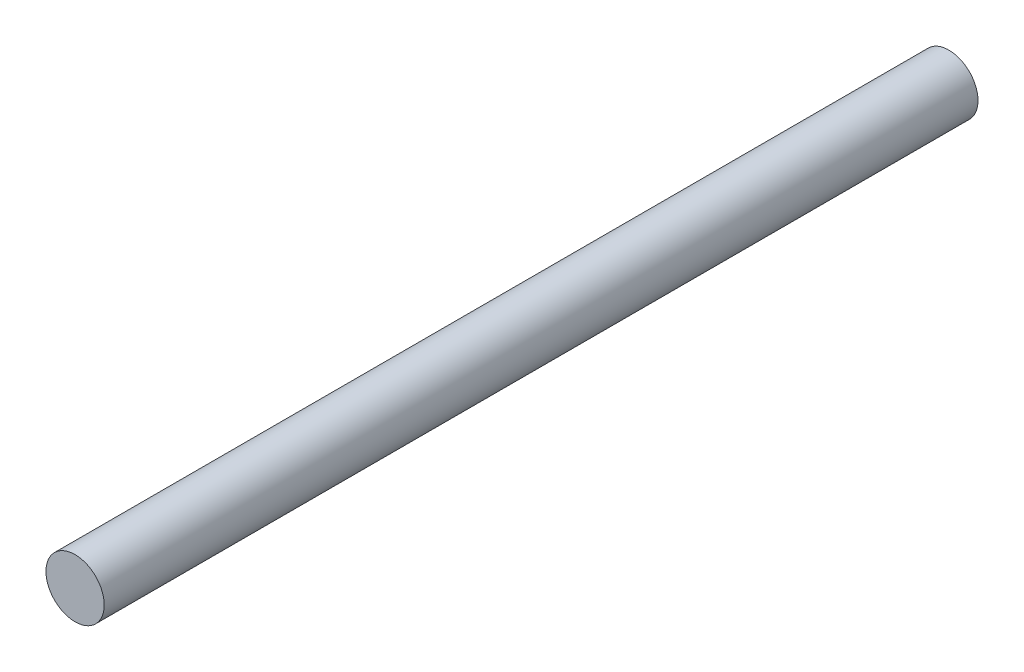
SolidWorks part; units mm, degrees
ref_plane "Front Plane" through (0, 0, 0) normal (0, 0, 1) x (1, 0, 0)
ref_plane "Top Plane" through (0, 0, 0) normal (0, 1, 0) x (1, 0, 0)
ref_plane "Right Plane" through (0, 0, 0) normal (1, 0, 0) x (0, 0, -1)
sketch "Sketch1" plane through (0, 0, 0) normal (0, 0, 1) x (1, 0, 0)
  circle A0 centre (0, 0) radius 25.4
  dimension "D1" = 50.8
extrude "Boss-Extrude1" add sketch "Sketch1" along normal blind 762
